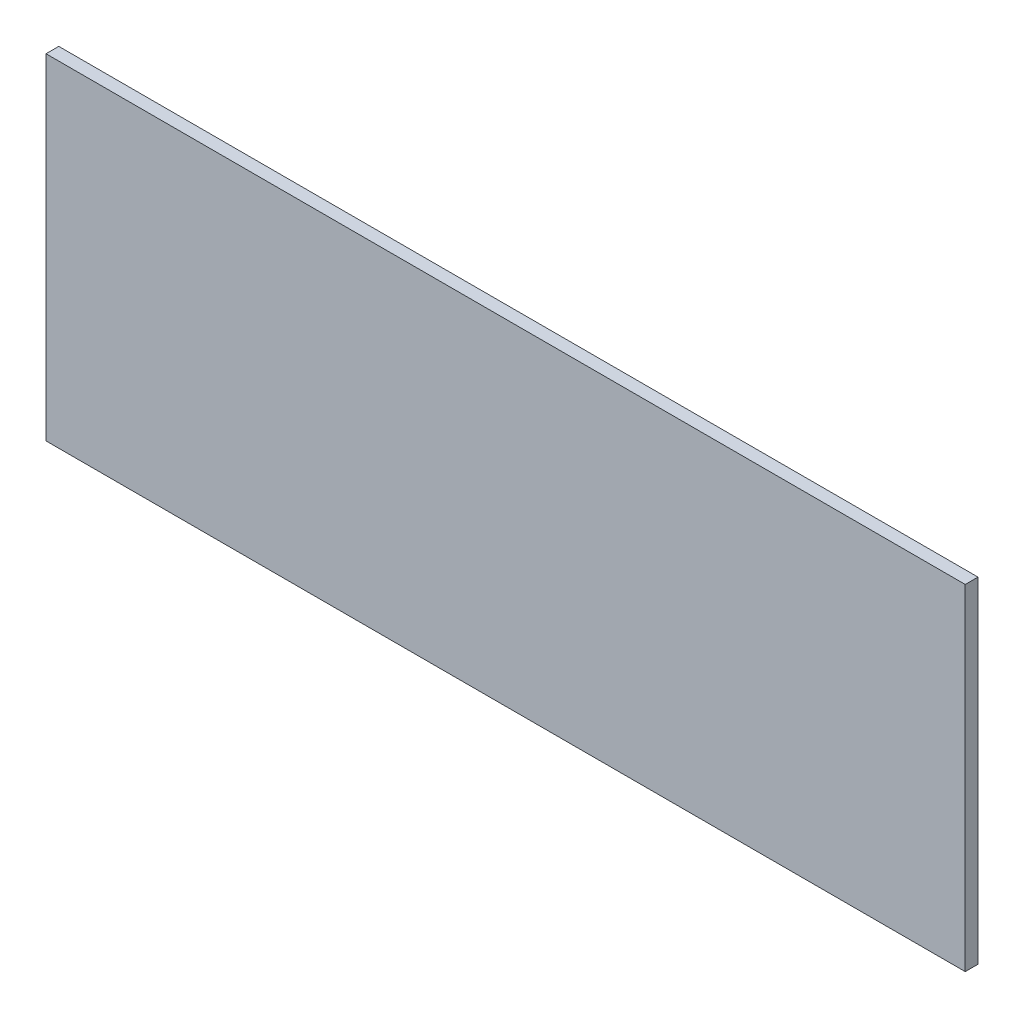
SolidWorks part; units mm, degrees
material "Balsa"
ref_plane "Front Plane" through (0, 0, 0) normal (0, 0, 1) x (1, 0, 0)
ref_plane "Top Plane" through (0, 0, 0) normal (0, 1, 0) x (1, 0, 0)
ref_plane "Right Plane" through (0, 0, 0) normal (1, 0, 0) x (0, 0, -1)
sketch "Sketch1" plane through (0, 0, 0) normal (0, 0, 1) x (1, 0, 0)
  line L1 (0, 0) -> (228.6, 0)
  line L2 (0, 0) -> (0, 83.3882)
  line L3 (0, 83.3882) -> (228.6, 83.3882)
  line L4 (228.6, 0) -> (228.6, 83.3882)
  dimension "D1" = 228.6
  dimension "D2" = 83.3882
extrude "Boss-Extrude1" add sketch "Sketch1" along normal blind 3.175
